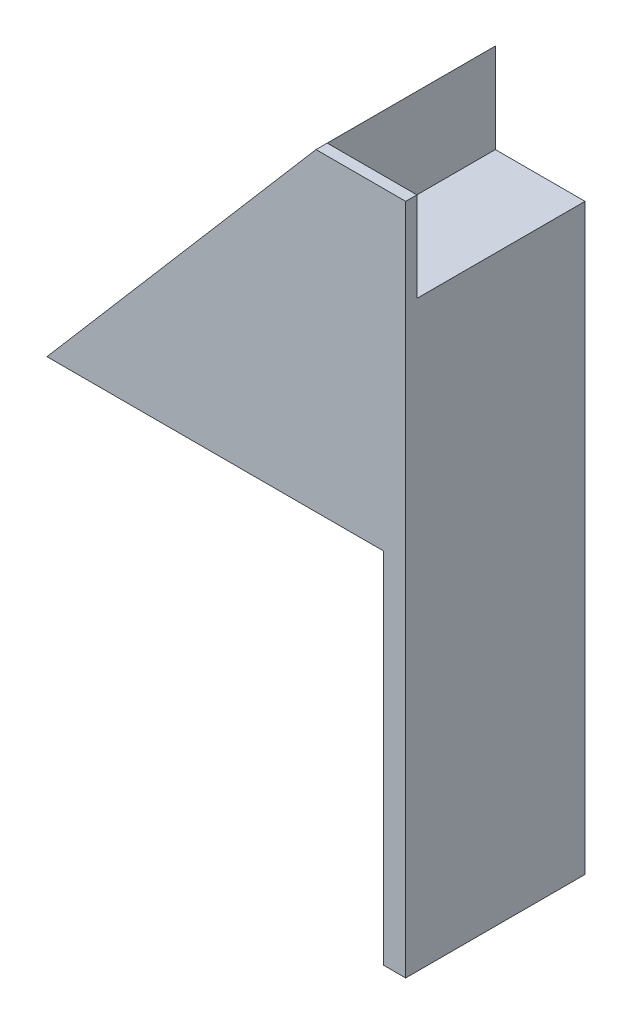
SolidWorks part; units mm, degrees
ref_plane "Front Plane" through (0, 0, 0) normal (0, 0, 1) x (1, 0, 0)
ref_plane "Top Plane" through (0, 0, 0) normal (0, 1, 0) x (1, 0, 0)
ref_plane "Right Plane" through (0, 0, 0) normal (1, 0, 0) x (0, 0, -1)
sketch "Sketch1" plane through (0, 0, 0) normal (0, 0, 1) x (1, 0, 0)
  line L0 (19.05, -50.8) -> (19.05, 0)
  line L1 (9.525, 44.45) -> (22.225, 44.45)
  line L2 (22.225, 31.75) -> (22.225, 44.45)
  line L3 (19.05, -50.8) -> (22.225, -50.8)
  line L4 (22.225, 31.75) -> (22.225, -50.8)
  line L7 (19.05, 0) -> (-28.575, 0)
  line L8 (-28.575, 0) -> (9.525, 44.45)
  point P0 (0, 0)
  dimension "D1" = 3.175
  dimension "D2" = 95.25
  dimension "D3" = 50.8
extrude "Boss-Extrude1" add sketch "Sketch1" along normal mid plane 25.4
sketch "Sketch2" plane through (0, 0, -12.7) normal (0, 0, -1) x (-1, 0, 0)
  line L1 (-22.225, 44.45) -> (-9.525, 44.45)
  line L2 (-22.225, 44.45) -> (-22.225, 31.75)
  line L3 (-22.225, 31.75) -> (-9.525, 31.75)
  line L4 (-9.525, 44.45) -> (-9.525, 31.75)
  dimension "D1" = 12.7
  dimension "D2" = 12.7
extrude "Cut-Extrude1" cut sketch "Sketch2" against normal blind 23.8125
